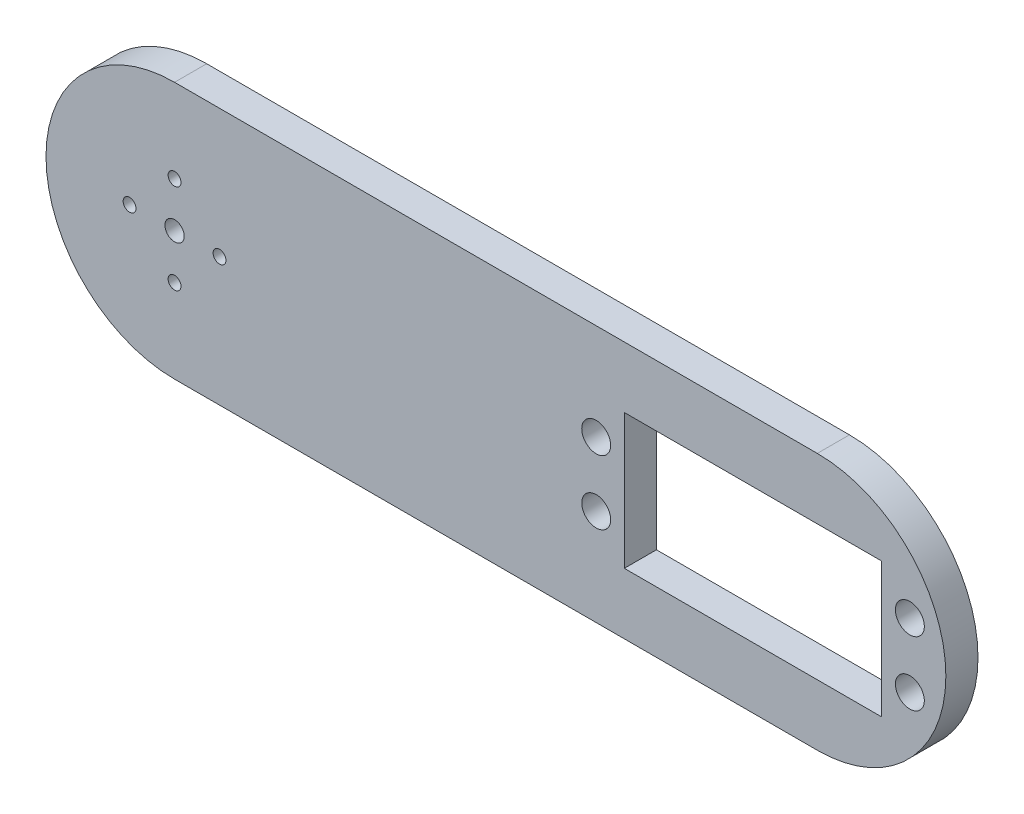
SolidWorks part; units mm, degrees
material "Acrylic (Medium-high impact)"
ref_plane "Front Plane" through (0, 0, 0) normal (0, 0, 1) x (1, 0, 0)
ref_plane "Top Plane" through (0, 0, 0) normal (0, 1, 0) x (1, 0, 0)
ref_plane "Right Plane" through (0, 0, 0) normal (1, 0, 0) x (0, 0, -1)
sketch "Sketch1" plane through (0, 0, 0) normal (0, 1, 0) x (1, 0, 0)
  line L0 (100, -20) -> (0, -20)
  line L2 (0, 20) -> (100, 20)
  line L3 (0, 0) -> (0, 6.474) construction
  line L4 (100, 0) -> (100, 8.2666) construction
  line L5 (100, 0) -> (185.7321, 0) construction
  arc A0 (0, 20) -> (0, -20) centre (0, 0) ccw
  arc A1 (100, -20) -> (100, 20) centre (100, 0) ccw
  circle A2 centre (100, -13.0415) radius 2.3527
  circle A3 centre (100, 13.0415) radius 2.3527
  dimension "D1" = 40
  dimension "D3" = 100
  dimension "D4" = 6.9585
  dimension "D5" = 100
  dimension "D2" = 2
extrude "Boss-Extrude1" add sketch "Sketch1" along normal blind 5 contours L2 A1 L0 A0
sketch "Sketch2" plane through (0, 5, 0) normal (0, 1, 0) x (1, 0, 0)
  circle A0 centre (0, 0) radius 1.5
  circle A1 centre (0, 7) radius 1
  circle A2 centre (0.001, 0.001) radius 1.5
  circle A3 centre (7.001, 0.001) radius 1
  circle A4 centre (0.002, 0) radius 1.5
  circle A5 centre (0.002, -7) radius 1
  circle A6 centre (0.001, -0.001) radius 1.5
  circle A7 centre (-6.999, -0.001) radius 1
  point P20 (0.001, 0)
  dimension "D1" = 3
  dimension "D2" = 2
  dimension "D4" = 7
  dimension "D3" = 4
extrude "Cut-Extrude1" cut sketch "Sketch2" against normal up to next contours A1 | A0 | A3 | A5 | A7
move or copy body "Body-Move/Copy1" bodies to move or copy 102 copy no rotation origin (0, 0, 0) rotation axis (1, 0, 0) rotation angle 90
sketch "Sketch19" plane through (0, 0, 5) normal (0, 0, 1) x (1, 0, 0)
  line L0 (100, 20) -> (100, -20) construction
  line L1 (120, 0) -> (170.0596, 0) construction
  line L3 (69.975, -10.5) -> (110.025, -10.5)
  line L4 (69.975, -10.5) -> (69.975, 10.5)
  line L5 (69.975, 10.5) -> (110.025, 10.5)
  line L6 (110.025, -10.5) -> (110.025, 10.5)
  line L7 (69.975, -10.5) -> (110.025, 10.5) construction
  line L8 (69.975, 10.5) -> (110.025, -10.5) construction
  arc A0 (100, -20) -> (100, 20) centre (100, 0) ccw construction
  circle A1 centre (114.4, -5) radius 2.25
  circle A2 centre (114.4, 5) radius 2.25
  circle A3 centre (65.6, 5) radius 2.25
  circle A4 centre (65.6, -5) radius 2.25
  point P0 (100, 0)
  point P21 (90, 0)
  dimension "D1" = 4.5
  dimension "D2" = 5
  dimension "D3" = 14.4
  dimension "D5" = 48.8
  dimension "D6" = 24.4
  dimension "D7" = 40.05
  dimension "D8" = 21
  dimension "D4" = 2
extrude "Cut-Extrude9" cut sketch "Sketch19" against normal through all
move or copy body "Body-Move/Copy2" bodies to move or copy 124 copy no translate (0, 0, -5)
